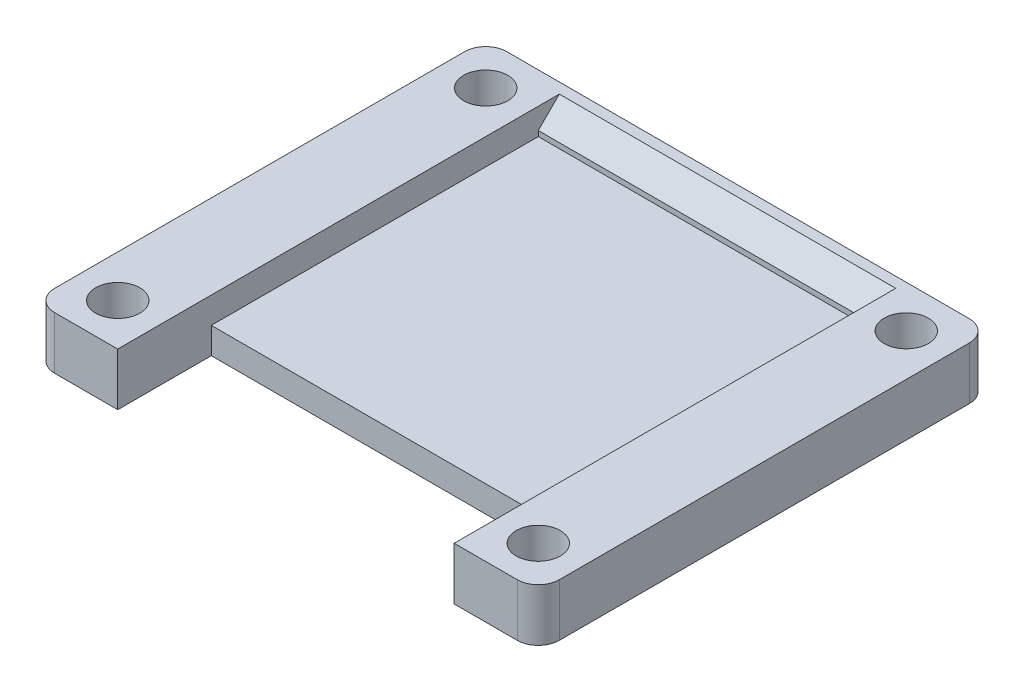
SolidWorks part; units mm, degrees
ref_plane "Спереди" through (0, 0, 0) normal (0, 0, 1) x (1, 0, 0)
ref_plane "Сверху" through (0, 0, 0) normal (0, 1, 0) x (1, 0, 0)
ref_plane "Справа" through (0, 0, 0) normal (1, 0, 0) x (0, 0, -1)
sketch "Эскиз1" plane through (0, 0, 0) normal (0, 1, 0) x (1, 0, 0)
  line L0 (-24, 43) -> (-24, -5) construction
  line L1 (-48, 43) -> (0, 43)
  line L2 (-48, 43) -> (-48, 0)
  line L3 (-48, 0) -> (0, 0)
  line L4 (0, 43) -> (0, 0)
  line L5 (-48, 21.5) -> (0, 21.5) construction
  point P6 (-24, 43)
  dimension "D1" = 43
  dimension "D2" = 48
extrude "Бобышка-Вытянуть1" add sketch "Эскиз1" against normal blind 5
sketch "Эскиз2" plane through (0, 0, 0) normal (0, 1, 0) x (1, 0, 0)
  line L0 (-48, 43) -> (-48, 0) construction
  line L1 (-40, 40) -> (-8, 40)
  line L2 (-40, 40) -> (-40, 0)
  line L3 (-40, 0) -> (-8, 0)
  line L4 (-8, 40) -> (-8, 0)
  line L5 (0, 0) -> (0, 43) construction
  line L7 (0, 43) -> (-48, 43) construction
  line L8 (-48, 0) -> (0, 0) construction
  line L9 (-48, 21.5) -> (0, 21.5) construction
  line L10 (-24, 43) -> (-24, -0.4774) construction
  point P16 (-24, 0)
  dimension "D1" = 8
  dimension "D2" = 8
  dimension "D4" = 3
extrude "Вырез-Вытянуть1" cut sketch "Эскиз2" against normal blind 2.5
sketch "Эскиз3" plane through (0, 0, 0) normal (0, 1, 0) x (1, 0, 0)
  line L0 (-48, 21.5) -> (0, 21.5) construction
  line L1 (-48, 43) -> (-48, 0) construction
  line L2 (0, 0) -> (0, 43) construction
  line L3 (-24, 43) -> (-24, 0) construction
  line L4 (0, 43) -> (-48, 43) construction
  line L5 (-40, 0) -> (-8, 0) construction
  circle A0 centre (-44, 39) radius 2.1
  circle A1 centre (-4, 39) radius 2.1
  circle A2 centre (-4, 4) radius 2.1
  circle A3 centre (-44, 4) radius 2.1
  dimension "D1" = 4.2
  dimension "D2" = 4
  dimension "D3" = 4
extrude "Вырез-Вытянуть2" cut sketch "Эскиз3" against normal through all
fillet "Скругление1" radius 2 4 edges at (-48, -2.5, 0) (0, -2.5, 0) (0, -2.5, -43) (-48, -2.5, -43)
chamfer "Фаска2" distance 2 angle 45 1 edges at (-24, 0, -40)
sketch "Эскиз4" plane through (0, -2.5, 0) normal (0, 1, 0) x (1, 0, 0)
  line L0 (-8, 0) -> (-8, 42) construction
  line L1 (-40, 0) -> (-8, 0)
  line L2 (-40, 0) -> (-40, 8.9)
  line L3 (-40, 8.9) -> (-8, 8.9)
  line L4 (-8, 0) -> (-8, 8.9)
  circle A5 centre (-4, 39) radius 2.1 construction
  dimension "D1" = 28
extrude "Вырез-Вытянуть3" cut sketch "Эскиз4" against normal through all
